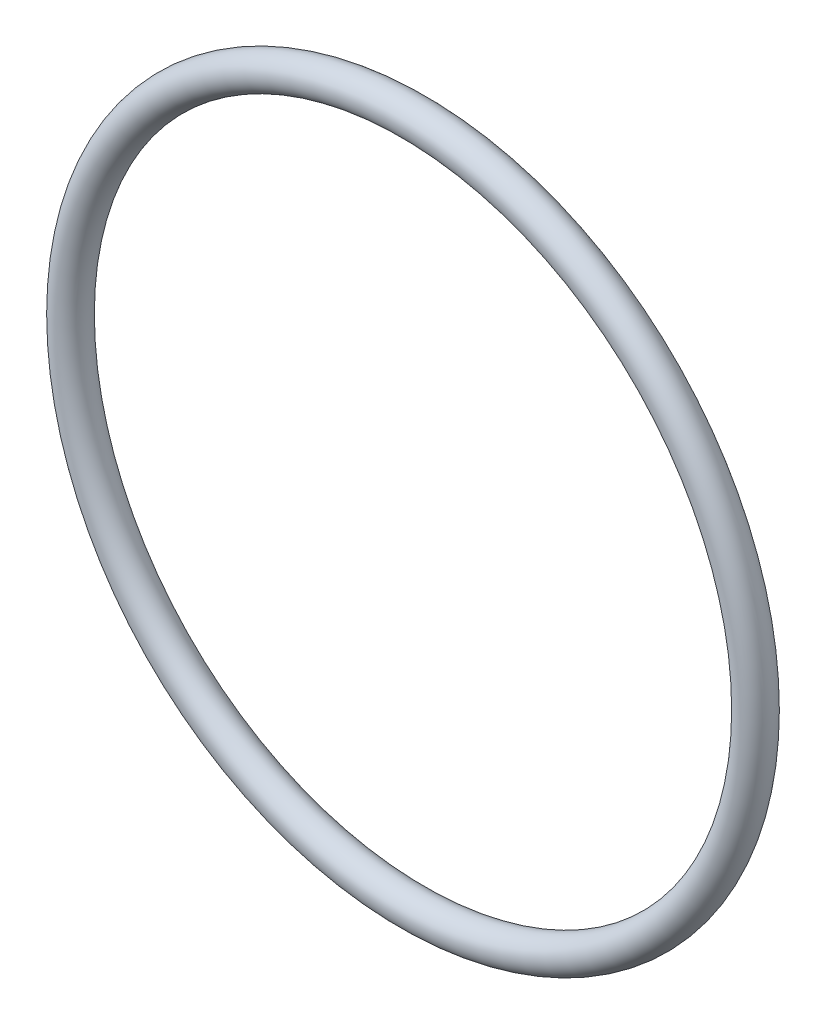
SolidWorks part; units mm, degrees
ref_plane "Front Plane" through (0, 0, 0) normal (0, 0, 1) x (1, 0, 0)
ref_plane "Top Plane" through (0, 0, 0) normal (0, 1, 0) x (1, 0, 0)
ref_plane "Right Plane" through (0, 0, 0) normal (1, 0, 0) x (0, 0, -1)
sketch "Sketch1" plane through (0, 0, 0) normal (0, 0, 1) x (1, 0, 0)
  line L0 (-27.8511, 0) -> (27.8511, 0) construction
  line L1 (-25.2349, 0) -> (25.2349, 0) construction
  line L2 (-19.6937, 19.6937) -> (19.6937, -19.6937) construction
  point P3 (25.2349, 0)
  point P4 (0, 0)
  point P8 (0, 0)
  point P9 (0, 0)
  point P10 (-27.8511, 0)
  point P11 (-25.2349, 0)
  point P14 (0, 0)
  point P15 (19.6937, -19.6937)
  point P16 (27.8511, 0)
  dimension "Actual OD" = 55.7022
  dimension "Actual ID" = 50.4698
  dimension "Actual Width" = 2.6162
  dimension "D1" = 45
sketch "Sketch2" plane through (0, 0, 0) normal (0, 1, 0) x (1, 0, 0)
  line L0 (-27.8511, 0) -> (27.8511, 0) construction
  line L1 (-26.543, 1.3081) -> (-26.543, -1.3081) construction
  line L2 (0, -1.3081) -> (0, 1.3081) construction
  circle A0 centre (-26.543, 0) radius 1.3081
  point P12 (0, 0)
revolve "Revolve1" add sketch "Sketch2" angle 360 about L2
sketch "Sketch3" plane through (0, 0, 0) normal (1, 0, 0) x (0, 0, -1)
  line L0 (-1.3081, 0) -> (1.3081, 0) construction
  line L1 (-1.3081, -18.9262) -> (-1.3081, 18.9262) construction
  point P4 (0, 0)
  point P7 (-1.3081, 0)
  point P9 (-1.3081, -18.9262)
  dimension "D1" = 2.6162
  dimension "D2" = 37.8524
equation "\"D1@Sketch3\"=\"Actual Width@Sketch1\""
equation "\"D2@Sketch3\"=\"Actual ID@Sketch1\"*.75"
